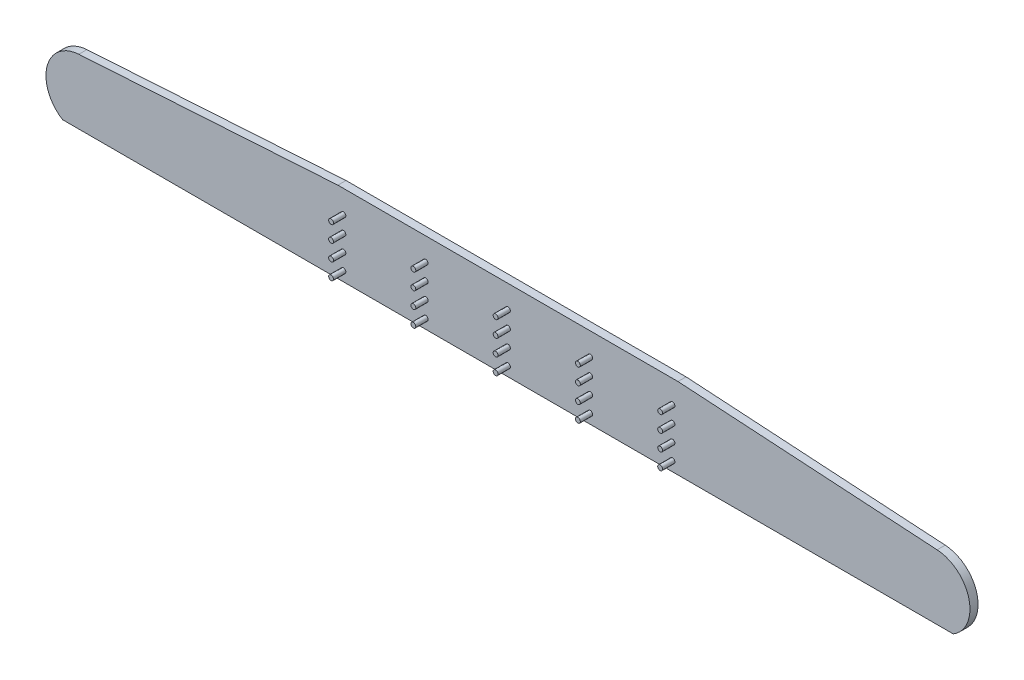
SolidWorks part; units mm, degrees
ref_plane "Front Plane" through (0, 0, 0) normal (0, 0, 1) x (1, 0, 0)
ref_plane "Top Plane" through (0, 0, 0) normal (0, 1, 0) x (1, 0, 0)
ref_plane "Right Plane" through (0, 0, 0) normal (1, 0, 0) x (0, 0, -1)
sketch "Sketch3" plane through (0, 0, 0) normal (0, 0, 1) x (1, 0, 0)
  line L0 (105, -25) -> (275, -25)
  line L1 (-105, 25) -> (105, 25)
  line L2 (-105, 25) -> (-105, -25)
  line L3 (-105, -25) -> (105, -25)
  line L4 (105, 25) -> (105, -25)
  line L5 (-105, 25) -> (105, -25) construction
  line L6 (-105, -25) -> (105, 25) construction
  line L7 (105, 25) -> (265, 15)
  line L8 (265, 15) -> (265, -25)
  line L9 (0, 0) -> (0, 149.1164) construction
  line L10 (-265, 15) -> (-265, -25)
  line L11 (-105, -25) -> (-275, -25)
  line L12 (-105, 25) -> (-265, 15)
  arc A0 (265, 15) -> (275, -25) centre (263.6508, -6.5873) cw
  arc A1 (-265, 15) -> (-275, -25) centre (-263.6508, -6.5873) ccw
  point P0 (0, 0)
  dimension "D1" = 210
  dimension "D2" = 50
  dimension "D3" = 170
  dimension "D4" = 160
  dimension "D5" = 10
extrude "Boss-Extrude1" add sketch "Sketch3" along normal blind 5 contours L2 L12 L10 L11 | L10 A1 L11 | L4 L1 L2 L3 | L8 L7 L4 L0 | A0 L8 L0
sketch "Sketch8" plane through (0, 0, 5) normal (0, 0, 1) x (1, 0, 0)
  line L0 (-265, 15) -> (-265, -25) construction
  line L1 (-105, 25) -> (-265, 15) construction
  line L2 (-105, -25) -> (-275, -25) construction
  line L3 (265, 15) -> (265, -25) construction
  line L4 (105, 25) -> (265, 15) construction
  line L5 (105, -25) -> (275, -25) construction
  line L6 (-105, 25) -> (-105, -25) construction
  line L7 (-105, -25) -> (105, -25) construction
  line L8 (-105, 25) -> (105, 25) construction
  line L9 (105, 25) -> (105, -25) construction
  line L10 (-265, 15) -> (-265, -25)
  line L11 (-105, 25) -> (-265, 15)
  line L12 (-105, -25) -> (-275, -25)
  line L13 (265, 15) -> (265, -25)
  line L14 (105, 25) -> (265, 15)
  line L15 (105, -25) -> (275, -25)
  line L16 (-105, 25) -> (-105, -25)
  line L17 (-105, -25) -> (105, -25)
  line L18 (-105, 25) -> (105, 25)
  line L19 (105, 25) -> (105, -25)
  arc A0 (-265, 15) -> (-275, -25) centre (-263.6508, -6.5873) ccw construction
  arc A1 (275, -25) -> (265, 15) centre (263.6508, -6.5873) ccw construction
  arc A2 (-265, 15) -> (-275, -25) centre (-263.6508, -6.5873) ccw
  arc A3 (275, -25) -> (265, 15) centre (263.6508, -6.5873) ccw
  circle A4 centre (0, 11) radius 1.5
  circle A5 centre (0, 1) radius 1.5
  circle A6 centre (0, -9) radius 1.5
  circle A7 centre (0, -19) radius 1.5
  circle A8 centre (50.8, 11) radius 1.5
  circle A9 centre (50.8, -9) radius 1.5
  circle A10 centre (50.8, 1) radius 1.5
  circle A11 centre (50.8, -19) radius 1.5
  circle A12 centre (101.6, 11) radius 1.5
  circle A13 centre (101.6, -9) radius 1.5
  circle A14 centre (101.6, 1) radius 1.5
  circle A15 centre (101.6, -19) radius 1.5
  circle A16 centre (-50.8, 11) radius 1.5
  circle A17 centre (-50.8, 1) radius 1.5
  circle A18 centre (-50.8, -9) radius 1.5
  circle A19 centre (-50.8, -19) radius 1.5
  circle A20 centre (-101.6, 11) radius 1.5
  circle A21 centre (-101.6, 1) radius 1.5
  circle A22 centre (-101.6, -9) radius 1.5
  circle A23 centre (-101.6, -19) radius 1.5
  dimension "D1" = 14
  dimension "D2" = 10
  dimension "D3" = 10
  dimension "D4" = 10
  dimension "D5" = 3
  dimension "D6" = 3
extrude "Boss-Extrude2" add sketch "Sketch8" along normal blind 7.62 contours A20 | A21 | A22 | A23 | A19 | A18 | A17 | A16 | A4 | A5 | A6 | A7 | A11 | A9 | A10 | A8 | A12 | A14 | A13 | A15
